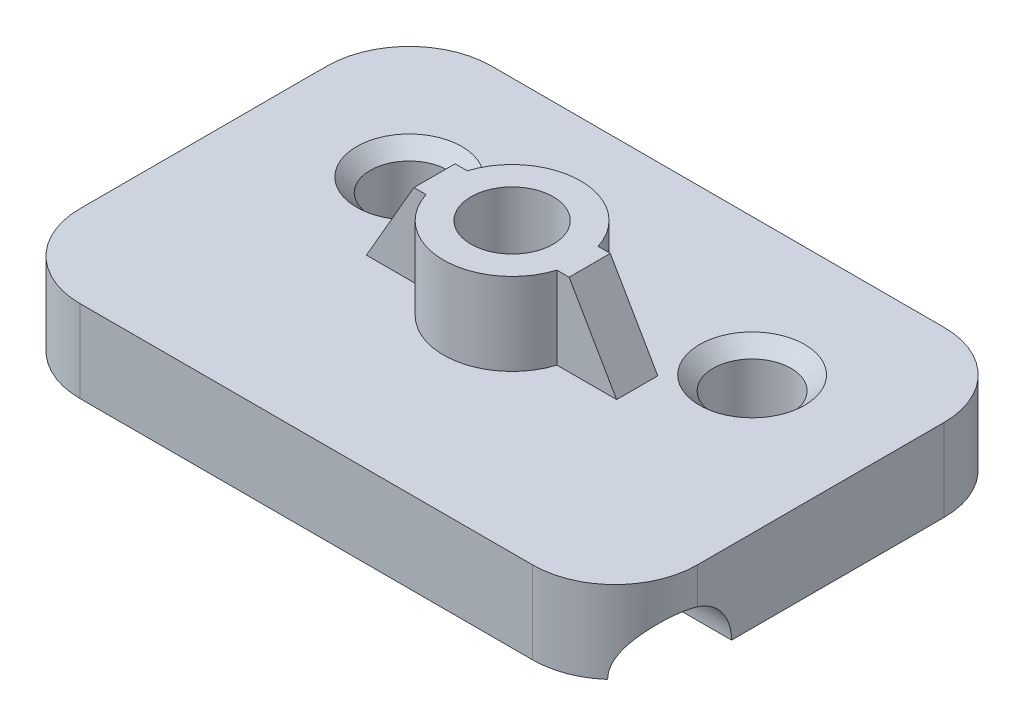
SolidWorks part; units mm, degrees
ref_plane "Ön Düzlem" through (0, 0, 0) normal (0, 0, 1) x (1, 0, 0)
ref_plane "Üst Düzlem" through (0, 0, 0) normal (0, 1, 0) x (1, 0, 0)
ref_plane "Sağ Düzlem" through (0, 0, 0) normal (1, 0, 0) x (0, 0, -1)
sketch "Çizim1" plane through (0, 0, 0) normal (0, 1, 0) x (1, 0, 0)
  line L1 (-16.5, 15) -> (16.5, 15)
  line L2 (-22.5, 9) -> (-22.5, -9)
  line L3 (-16.5, -15) -> (16.5, -15)
  line L4 (22.5, 9) -> (22.5, -9)
  line L5 (-22.5, 15) -> (22.5, -15) construction
  line L6 (-22.5, -15) -> (22.5, 15) construction
  circle A0 centre (0, 0) radius 3
  arc A1 (-22.5, 9) -> (-16.5, 15) centre (-16.5, 9) cw
  arc A2 (22.5, 9) -> (16.5, 15) centre (16.5, 9) ccw
  arc A3 (16.5, -15) -> (22.5, -9) centre (16.5, -9) ccw
  arc A4 (-16.5, -15) -> (-22.5, -9) centre (-16.5, -9) cw
  dimension "D1" = 6
  dimension "D4" = 6
  dimension "D2" = 22.5
  dimension "D3" = 30
extrude "Yükseklik-Ekstrüzyon1" add sketch "Çizim1" along normal blind 6
sketch "Çizim2" plane through (0, 6, 0) normal (0, 1, 0) x (1, 0, 0)
  circle A0 centre (0, 0) radius 3
  circle A1 centre (0, 0) radius 5
  dimension "D1" = 2
extrude "Yükseklik-Ekstrüzyon2" add sketch "Çizim2" along normal blind 6
sketch "Çizim4" plane through (0, 0, 0) normal (0, 0, 1) x (1, 0, 0)
  line L0 (-5.6578, 12) -> (-3.7985, 12)
  line L1 (-5.6578, 12) -> (-9.1219, 6)
  line L2 (-16.5, 6) -> (16.5, 6) construction
  line L3 (5, 12) -> (-5, 12) construction
  line L4 (-3.7985, 12) -> (-3.7985, 6)
  line L5 (-3.7985, 6) -> (-9.1219, 6)
  line L6 (0, 14.6841) -> (0, 2.6623) construction
  line L7 (3.7985, 12) -> (3.7985, 6)
  line L8 (5.6578, 12) -> (3.7985, 12)
  line L9 (5.6578, 12) -> (9.1219, 6)
  line L10 (3.7985, 6) -> (9.1219, 6)
  dimension "D1" = 30
extrude "Yükseklik-Ekstrüzyon3" add sketch "Çizim4" along normal mid plane 3
sketch "Çizim5" plane through (0, 0, 0) normal (1, 0, 0) x (0, 0, -1)
  line L0 (-15, 0) -> (-9, 0) construction
  line L1 (-15, 6) -> (-15, 0) construction
  circle A0 centre (-10, 0) radius 3.5
  dimension "D2" = 7
  dimension "D1" = 5
extrude "Kes-Ekstrüzyon1" cut sketch "Çizim5" against normal up to surface and the other way up to surface up to face at (-22.5, 3, 0) other way up to face at (22.5, 3, 0)
sketch "Çizim6" plane through (0, 0, 0) normal (0, -1, 0) x (1, 0, 0)
  line L0 (-22.5, -9) -> (-22.5, 6.5) construction
  line L1 (22.5, 6.5) -> (22.5, -9) construction
  line L2 (16.5, -15) -> (-16.5, -15) construction
  circle A0 centre (-12.5, -5) radius 2.8382
  circle A1 centre (12.5, -5) radius 2.8382
  dimension "D1" = 10
  dimension "D2" = 10
  dimension "D3" = 10
extrude "Kes-Ekstrüzyon2" cut sketch "Çizim6" against normal blind 44
chamfer "Pah1" distance 1 angle 45 4 edges at (12.5, 0, -7.8382) (-12.5, 0, -7.8382) (-12.5, 6, -7.8382) (12.5, 6, -7.8382)
